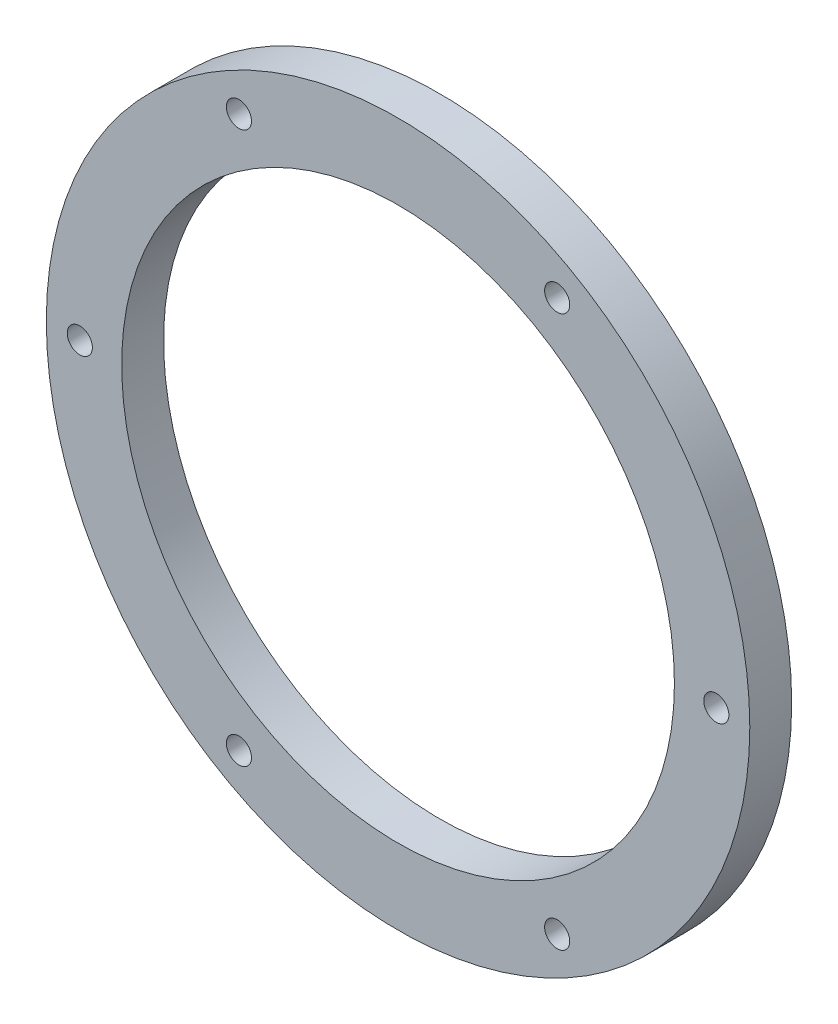
SolidWorks part; units mm, degrees
material "Acrylic (Medium-high impact)"
ref_plane "Front Plane" through (0, 0, 0) normal (0, 0, 1) x (1, 0, 0)
ref_plane "Top Plane" through (0, 0, 0) normal (0, 1, 0) x (1, 0, 0)
ref_plane "Right Plane" through (0, 0, 0) normal (1, 0, 0) x (0, 0, -1)
sketch "Sketch1" plane through (0, 0, 0) normal (0, 0, 1) x (1, 0, 0)
  circle A0 centre (0, 0) radius 42
  circle A1 centre (0, 0) radius 33
extrude "Boss-Extrude1" add sketch "Sketch1" along normal blind 5
sketch "Sketch2" plane through (0, 0, 0) normal (0, 0, -1) x (-1, 0, 0)
  line L0 (-73.7646, 0) -> (58.2851, 0) construction
  line L1 (27.966, 48.4385) -> (0, 0) construction
  line L2 (0, 0) -> (-33.8549, -58.6384) construction
  line L3 (0, 0) -> (-31.6308, 54.7862) construction
  line L4 (-31.6308, 54.7862) -> (37.1164, -64.2875) construction
  circle A0 centre (0, 0) radius 38 construction
  circle A1 centre (-19, 32.909) radius 1.5
  circle A2 centre (0, 0) radius 32.5 construction
  circle A3 centre (19, 32.909) radius 1.5
  circle A4 centre (38, 0) radius 1.5
  circle A5 centre (19, -32.909) radius 1.5
  circle A6 centre (-19, -32.909) radius 1.5
  circle A7 centre (-38, 0) radius 1.5
  dimension "D1" = 60
  dimension "D2" = 60
extrude "Cut-Extrude1" cut sketch "Sketch2" against normal blind 11
